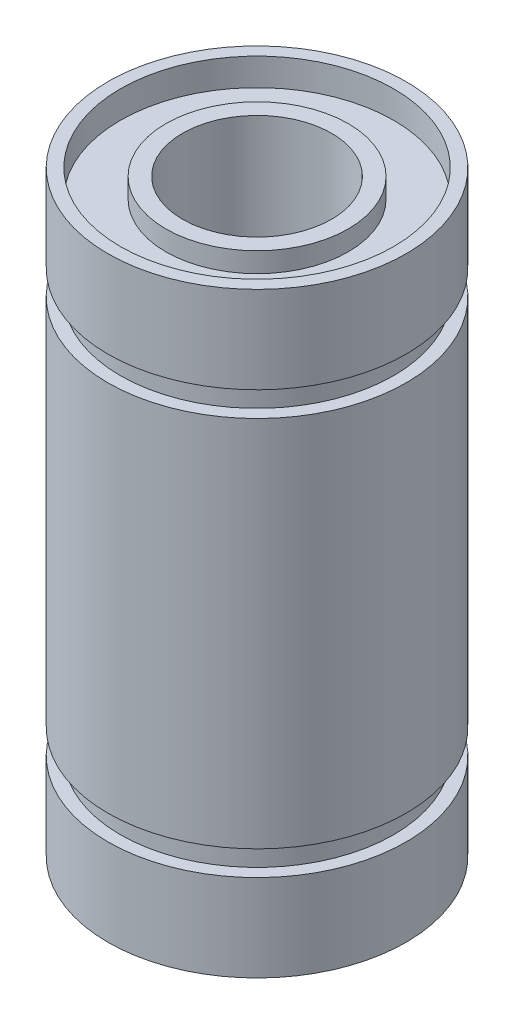
SolidWorks part; units mm, degrees
material "Chrome Stainless Steel"
ref_plane "Front Plane" through (0, 0, 0) normal (0, 0, 1) x (1, 0, 0)
ref_plane "Top Plane" through (0, 0, 0) normal (0, 1, 0) x (1, 0, 0)
ref_plane "Right Plane" through (0, 0, 0) normal (1, 0, 0) x (0, 0, -1)
sketch "Sketch1" plane through (0, 0, 0) normal (0, 1, 0) x (1, 0, 0)
  circle A0 centre (0, 0) radius 6
  dimension "D1" = 12
extrude "Boss-Extrude1" add sketch "Sketch1" along normal mid plane 24
sketch "Sketch2" plane through (0, 12, 0) normal (0, 1, 0) x (1, 0, 0)
  circle A0 centre (0, 0) radius 3
  dimension "D1" = 6
extrude "Cut-Extrude1" cut sketch "Sketch2" against normal blind 24
sketch "Sketch3" plane through (0, 12, 0) normal (0, 1, 0) x (1, 0, 0)
  circle A0 centre (0, 0) radius 5.5
  circle A1 centre (0, 0) radius 6
  circle A2 centre (0, 0) radius 6
  dimension "D1" = 0
  dimension "D2" = 0.5
extrude "Cut-Extrude2" cut sketch "Sketch3" against normal blind 1 from offset 3.5 offset against normal yes
sketch "Sketch4" plane through (0, 0, 0) normal (1, 0, 0) x (0, 0, -1)
  line L0 (3, 12) -> (3, 11.7)
  line L1 (3, 11.7) -> (3.6708, 11.7)
  line L2 (3.6708, 11.7) -> (3.6708, 10.9)
  line L3 (3.6708, 10.9) -> (5.5, 10.9)
  line L4 (5.5, 10.9) -> (5.5, 12)
  line L5 (5.5, 12) -> (3, 12)
  line L6 (0, 10.5) -> (0, -2.243) construction
  dimension "D1" = 0.3
  dimension ".8" = 2.5
  dimension "D5" = 0.8
revolve "Cut-Revolve1" cut sketch "Sketch4" angle 360 about L6
mirror "Mirror1" about plane through (0, 0, 0) normal (0, 1, 0) of "Cut-Revolve1", "Cut-Extrude2"
